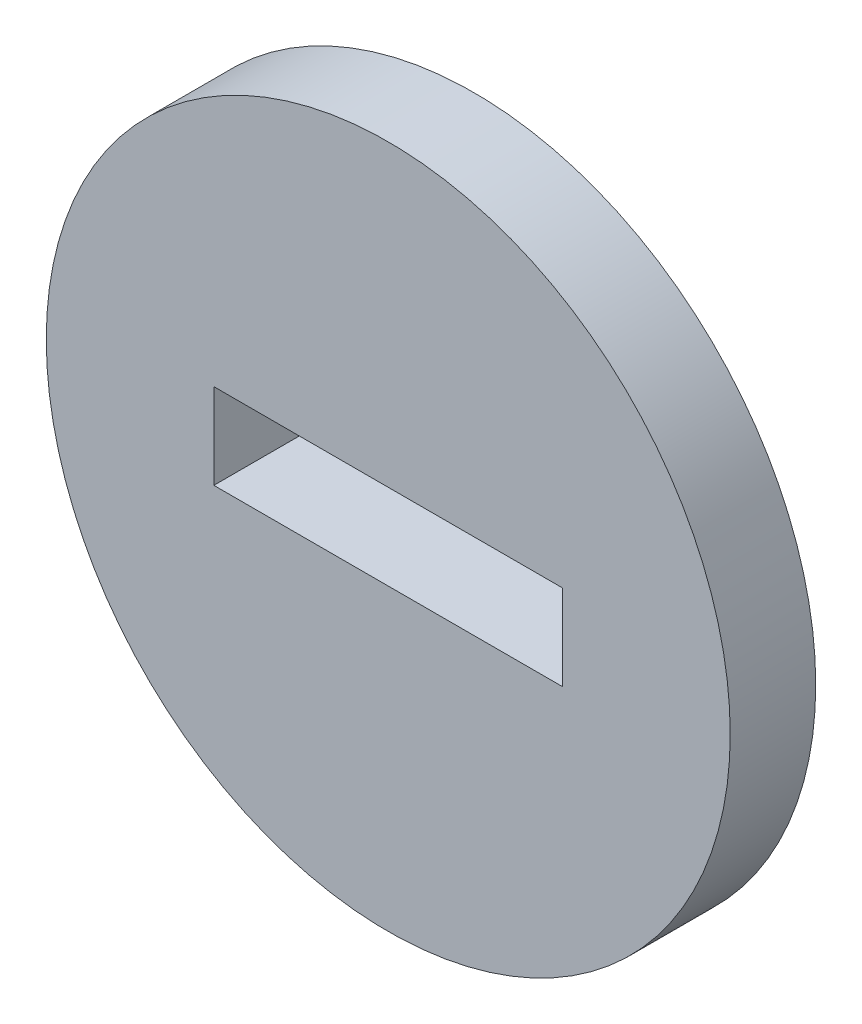
SolidWorks part; units mm, degrees
ref_plane "Front Plane" through (0, 0, 0) normal (0, 0, 1) x (1, 0, 0)
ref_plane "Top Plane" through (0, 0, 0) normal (0, 1, 0) x (1, 0, 0)
ref_plane "Right Plane" through (0, 0, 0) normal (1, 0, 0) x (0, 0, -1)
sketch "Sketch1" plane through (0, 0, 0) normal (0, 0, 1) x (1, 0, 0)
  line L1 (-5.1, -1.25) -> (5.1, -1.25)
  line L2 (-5.1, -1.25) -> (-5.1, 1.25)
  line L3 (-5.1, 1.25) -> (5.1, 1.25)
  line L4 (5.1, -1.25) -> (5.1, 1.25)
  line L5 (-5.1, -1.25) -> (5.1, 1.25) construction
  line L6 (-5.1, 1.25) -> (5.1, -1.25) construction
  circle A0 centre (0, 0) radius 10
extrude "Boss-Extrude1" add sketch "Sketch1" along normal blind 2.5
